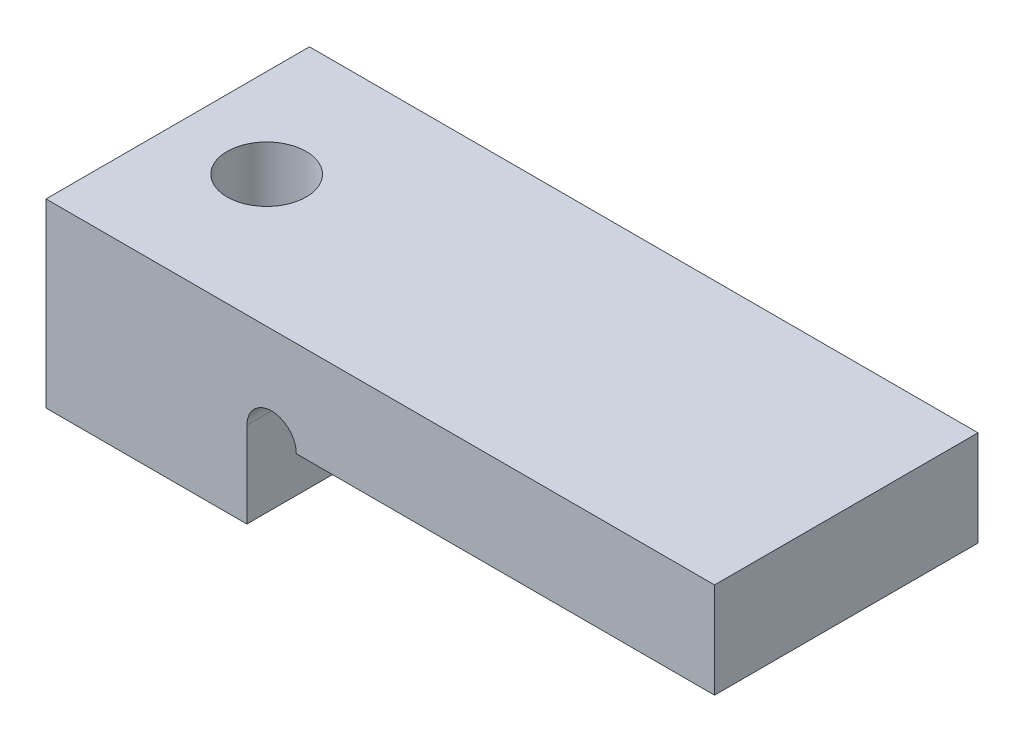
SolidWorks part; units mm, degrees
ref_plane "Front Plane" through (0, 0, 0) normal (0, 0, 1) x (1, 0, 0)
ref_plane "Top Plane" through (0, 0, 0) normal (0, 1, 0) x (1, 0, 0)
ref_plane "Right Plane" through (0, 0, 0) normal (1, 0, 0) x (0, 0, -1)
sketch "Sketch1" plane through (0, 0, 0) normal (0, 0, 1) x (1, 0, 0)
  line L4 (0, 0) -> (6.1, 0)
  line L17 (6.1, 2.6) -> (6.1, 0)
  line L21 (6.1, 2.6) -> (20.3, 2.6)
  line L23 (20.3, 5.5) -> (20.3, 2.6)
  line L24 (0, 0) -> (0, 5.5)
  line L25 (20.3, 5.5) -> (0, 5.5)
  dimension "D3" = 6.1
  dimension "D4" = 5.5
  dimension "D6" = 14.2
  dimension "D10" = 2.6
extrude "Boss-Extrude2" add sketch "Sketch1" along normal mid plane 8
sketch "Sketch2" plane through (0, 0, 0) normal (0, 1, 0) x (1, 0, 0)
  line L0 (0, 0) -> (2.7, 0) construction
  line L1 (0, -4) -> (0, 4) construction
  circle A0 centre (2.7, 0) radius 1.2
  dimension "D1" = 2.4
  dimension "D2" = 2.7
extrude "Cut-Extrude2" cut sketch "Sketch2" against normal through all and the other way through all
sketch "Sketch3" plane through (0, 0, 0) normal (0, 0, 1) x (1, 0, 0)
  line L0 (6.1, 2.6) -> (20.3, 2.6) construction
  circle A0 centre (6.85, 2.6) radius 0.75
  dimension "D1" = 1.5
extrude "Cut-Extrude3" cut sketch "Sketch3" against normal through all both and the other way through all
